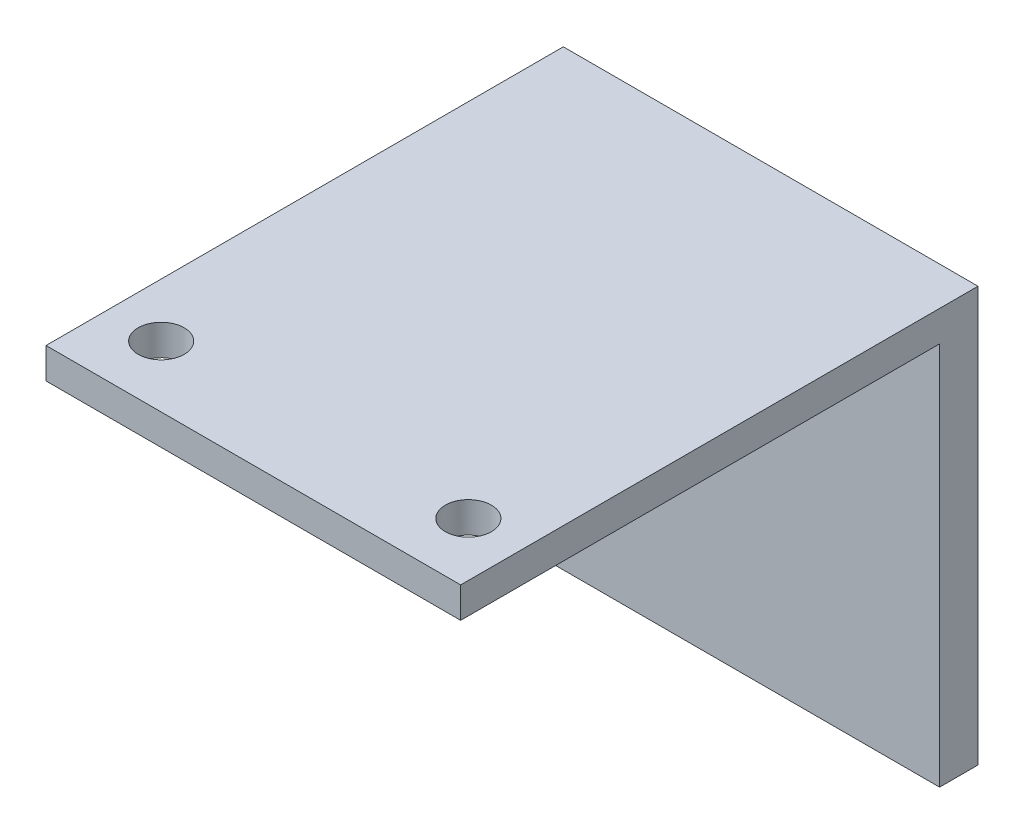
SolidWorks part; units mm, degrees
ref_plane "Plan de face" through (0, 0, 0) normal (0, 0, 1) x (1, 0, 0)
ref_plane "Plan de dessus" through (0, 0, 0) normal (0, 1, 0) x (1, 0, 0)
ref_plane "Plan de droite" through (0, 0, 0) normal (1, 0, 0) x (0, 0, -1)
sketch "Esquisse1" plane through (0, 0, 0) normal (0, 0, 1) x (1, 0, 0)
  line L1 (-27, -27) -> (27, -27)
  line L2 (-27, -27) -> (-27, 27)
  line L3 (-27, 27) -> (27, 27)
  line L4 (27, -27) -> (27, 27)
  line L5 (-27, -27) -> (27, 27) construction
  line L6 (-27, 27) -> (27, -27) construction
  line L7 (9, -27) -> (-9, -27)
  line L8 (9, -27) -> (9, 27)
  line L9 (9, 27) -> (-9, 27)
  line L10 (-9, -27) -> (-9, 27)
  line L11 (9, -27) -> (-9, 27) construction
  line L12 (9, 27) -> (-9, -27) construction
  circle A0 centre (9.88, 20) radius 3
  circle A1 centre (9.88, -20) radius 3
  point P0 (0, 0)
  point P7 (0, 0)
  dimension "D4" = 6
  dimension "D1" = 54
  dimension "D2" = 54
  dimension "D3" = 17.12
  dimension "D5" = 7
  dimension "D7" = 2
extrude "Boss.-Extru.1" add sketch "Esquisse1" along normal blind 67.37 contours L8 L1 L4 L3 | L1 L10 L3 L2 | L10 L1 L8 L3 A1 A0
sketch "Esquisse2" plane through (0, 0, 67.37) normal (0, 0, 1) x (1, 0, 0)
  line L8 (23, 23) -> (-23, 23)
  line L9 (-23, 23) -> (-23, -23)
  line L10 (-23, -23) -> (23, -23)
  line L11 (23, -23) -> (23, 23)
  line L12 (38.775, 23) -> (-47.1129, 23)
  line L13 (-47.1129, 23) -> (-47.1129, -35.7903)
  line L14 (-47.1129, -35.7903) -> (38.775, -35.7903)
  line L15 (38.775, -35.7903) -> (38.775, 23)
  dimension "D1" = 4
extrude "Enlèv. mat.-Extru.1" cut sketch "Esquisse2" against normal blind 62.37
sketch "Esquisse3" plane through (0, 23, 0) normal (0, -1, 0) x (1, 0, 0)
  line L0 (27, 67.37) -> (-27, 67.37) construction
  line L1 (-27, 67.37) -> (-27, 5) construction
  circle A0 centre (-20, 59.37) radius 3
  circle A1 centre (20, 59.37) radius 3
  dimension "D3" = 6
  dimension "D1" = 8
  dimension "D2" = 7
  dimension "D4" = 2
extrude "Enlèv. mat.-Extru.2" cut sketch "Esquisse3" against normal blind 62.37
hole_wizard "Dégagement M61" positions "Esquisse5" profile "Esquisse4" hole size "M6" standard "JIS" end condition through all
sketch "Esquisse5" plane through (0, 0, 0) normal (0, 0, -1) x (-1, 0, 0)
  point P0 (20.5628, -15.5)
  point P2 (20.5628, 16.5)
sketch "Esquisse4" plane through (-20.5628, -15.5, 0) normal (1, 0, 0) x (0, 1, 0)
  line L0 (0, 0) -> (0, 67.37)
  line L1 (0, 67.37) -> (3.3, 67.37)
  line L2 (3.3, 67.37) -> (3.3, 0)
  line L5 (3.3, 0) -> (0, 0)
  line L11 (0, -6.35) -> (0, 107.95) construction
  dimension "Diamètre du perçage jusqu'au prochain" = 6.6
  dimension "Profondeur du perçage jusqu'au prochain" = 67.37
